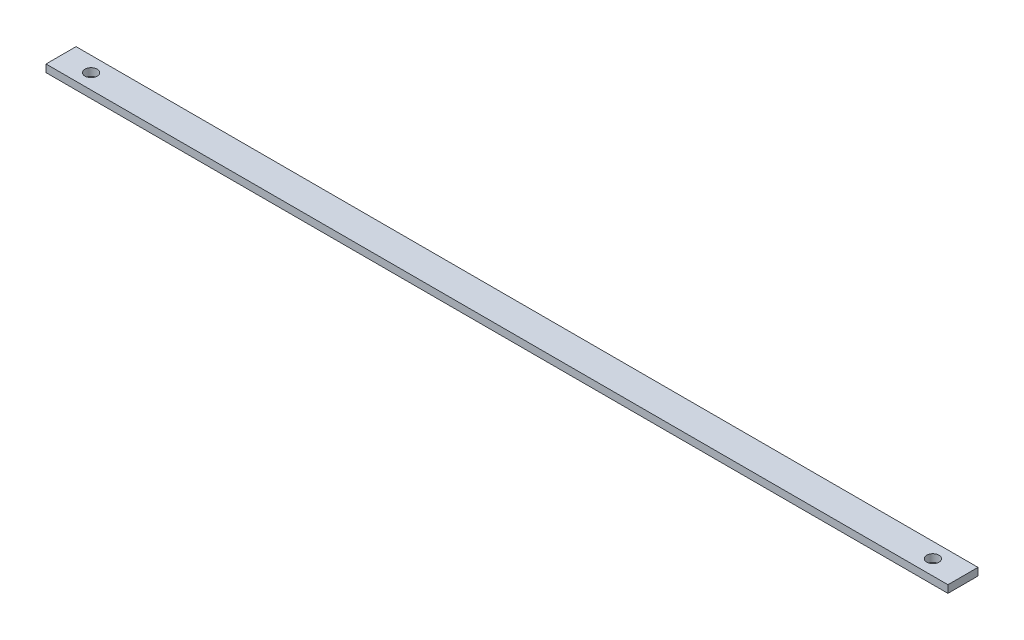
SolidWorks part; units mm, degrees
ref_plane "Front Plane" through (0, 0, 0) normal (0, 0, 1) x (1, 0, 0)
ref_plane "Top Plane" through (0, 0, 0) normal (0, 1, 0) x (1, 0, 0)
ref_plane "Right Plane" through (0, 0, 0) normal (1, 0, 0) x (0, 0, -1)
sketch "Sketch2" plane through (0, 0, 0) normal (0, 1, 0) x (1, 0, 0)
  line L5 (-381, 12.7) -> (381, 12.7)
  line L6 (-381, 12.7) -> (-381, -12.7)
  line L7 (-381, -12.7) -> (381, -12.7)
  line L8 (381, 12.7) -> (381, -12.7)
  line L9 (-381, 12.7) -> (381, -12.7) construction
  line L10 (-381, -12.7) -> (381, 12.7) construction
  point P0 (0, 0)
  dimension "D1" = 762
  dimension "D2" = 25.4
extrude "Boss-Extrude3" add sketch "Sketch2" along normal blind 6.35
sketch "Sketch5" plane through (0, 6.35, 0) normal (0, 1, 0) x (1, 0, 0)
  line L0 (0, 0) -> (0, -262.6771) construction
  circle A0 centre (355.6, 0) radius 5.1594
  circle A1 centre (-355.6, 0) radius 5.1594
  point P3 (0, 0)
  dimension "D2" = 10.3187
  dimension "D1" = 355.6
extrude "Cut-Extrude1" cut sketch "Sketch5" against normal through all
